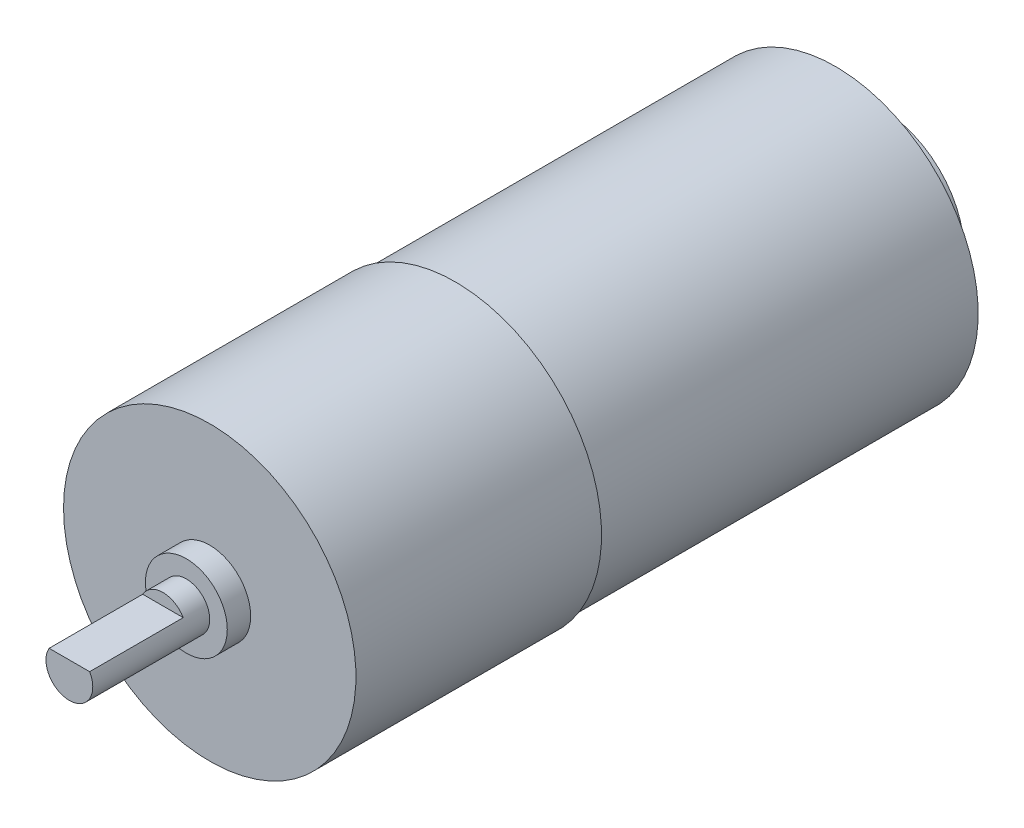
SolidWorks part; units mm, degrees
ref_plane "Plano frontal" through (0, 0, 0) normal (0, 0, 1) x (1, 0, 0)
ref_plane "Plano superior" through (0, 0, 0) normal (0, 1, 0) x (1, 0, 0)
ref_plane "Plano direito" through (0, 0, 0) normal (1, 0, 0) x (0, 0, -1)
sketch "Esboço1" plane through (0, 0, 0) normal (0, 0, 1) x (1, 0, 0)
  circle A0 centre (0, 0) radius 12.5
extrude "Ressalto-extrusão2" add sketch "Esboço1" along normal blind 21 contours A0
sketch "Esboço2" plane through (0, 0, 0) normal (0, 0, -1) x (-1, 0, 0)
  circle A0 centre (0, 0) radius 12.2
extrude "Ressalto-extrusão3" add sketch "Esboço2" along normal blind 31
sketch "Esboço3" plane through (0, 0, 21) normal (0, 0, 1) x (1, 0, 0)
  circle A0 centre (0, 0) radius 3.5
extrude "Ressalto-extrusão4" add sketch "Esboço3" along normal blind 2
sketch "Esboço4" plane through (0, 0, 23) normal (0, 0, 1) x (1, 0, 0)
  circle A0 centre (0, 0) radius 2
extrude "Ressalto-extrusão6" add sketch "Esboço4" along normal blind 10 contours A0
sketch "Esboço6" plane through (0, 0, 33) normal (0, 0, 1) x (1, 0, 0)
  line L0 (0, 2) -> (3.69, 2)
  line L1 (3.69, 2) -> (3.69, 1)
  line L2 (3.69, 1) -> (-3.8251, 1)
  line L3 (-3.8251, 1) -> (-3.8251, 2)
  line L4 (-3.8251, 2) -> (0, 2)
  circle A0 centre (0, 0) radius 2 construction
  circle A1 centre (0, 0) radius 2 construction
extrude "Corte-extrusão1" cut sketch "Esboço6" against normal blind 8 contours L4 L0 L1 L2 L3
sketch "Esboço7" plane through (0, 0, -31) normal (0, 0, -1) x (-1, 0, 0)
  circle A0 centre (0, 0) radius 12.2
extrude "Ressalto-extrusão8" add sketch "Esboço7" along normal blind 1.5
sketch "Esboço8" plane through (0, 0, -32.5) normal (0, 0, -1) x (-1, 0, 0)
  circle A0 centre (0, 0) radius 0.75
extrude "Ressalto-extrusão9" add sketch "Esboço8" along normal blind 1
sketch "Esboço9" plane through (0, 0, -33.5) normal (0, 0, -1) x (-1, 0, 0)
  circle A0 centre (0, 0) radius 7
extrude "Ressalto-extrusão10" add sketch "Esboço9" along normal blind 3
